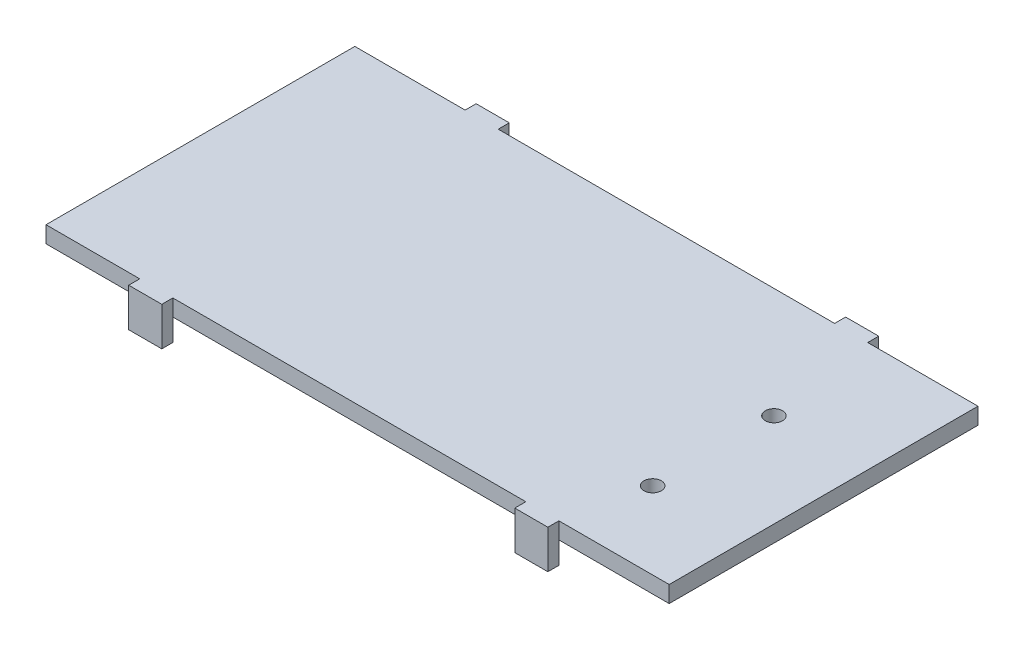
SolidWorks part; units mm, degrees
ref_plane "Front Plane" through (0, 0, 0) normal (0, 0, 1) x (1, 0, 0)
ref_plane "Top Plane" through (0, 0, 0) normal (0, 1, 0) x (1, 0, 0)
ref_plane "Right Plane" through (0, 0, 0) normal (1, 0, 0) x (0, 0, -1)
sketch "Sketch1" plane through (0, 0, 0) normal (0, 1, 0) x (1, 0, 0)
  line L1 (-75.3322, 26.3032) -> (68.1778, 26.3032)
  line L2 (-75.3322, 26.3032) -> (-75.3322, -44.8168)
  line L3 (-75.3322, -44.8168) -> (68.1778, -44.8168)
  line L4 (68.1778, 26.3032) -> (68.1778, -44.8168)
  dimension "D1" = 143.51
  dimension "D2" = 71.12
extrude "Boss-Extrude1" add sketch "Sketch1" along normal blind 3.81
sketch "Sketch2" plane through (0, 3.81, 0) normal (0, 1, 0) x (1, 0, 0)
  line L0 (68.1778, 26.3032) -> (-75.3322, 26.3032) construction
  line L1 (-49.9322, 26.3032) -> (-42.3122, 26.3032)
  line L2 (-49.9322, 26.3032) -> (-49.9322, 28.8432)
  line L3 (-49.9322, 28.8432) -> (-42.3122, 28.8432)
  line L4 (-42.3122, 26.3032) -> (-42.3122, 28.8432)
  line L5 (35.1578, 26.3032) -> (42.7778, 26.3032)
  line L6 (35.1578, 26.3032) -> (35.1578, 28.8432)
  line L7 (35.1578, 28.8432) -> (42.7778, 28.8432)
  line L8 (42.7778, 26.3032) -> (42.7778, 28.8432)
  line L9 (-53.7422, -47.3568) -> (-46.1222, -47.3568)
  line L10 (-53.7422, -47.3568) -> (-53.7422, -44.8168)
  line L11 (-53.7422, -44.8168) -> (-46.1222, -44.8168)
  line L12 (-46.1222, -47.3568) -> (-46.1222, -44.8168)
  line L13 (35.1578, -47.3568) -> (42.7778, -47.3568)
  line L14 (35.1578, -47.3568) -> (35.1578, -44.8168)
  line L15 (35.1578, -44.8168) -> (42.7778, -44.8168)
  line L16 (42.7778, -47.3568) -> (42.7778, -44.8168)
  line L17 (68.1778, -44.8168) -> (68.1778, 26.3032) construction
  line L18 (-75.3322, -44.8168) -> (68.1778, -44.8168) construction
  dimension "D1" = 7.62
  dimension "D2" = 2.54
  dimension "D3" = 0
  dimension "D4" = 2.54
  dimension "D5" = 7.62
  dimension "D6" = 7.62
  dimension "D7" = 2.54
  dimension "D8" = 7.62
  dimension "D9" = 2.54
  dimension "D10" = 25.4
  dimension "D11" = 0
  dimension "D12" = 0
  dimension "D13" = 121.92
extrude "Boss-Extrude3" add sketch "Sketch2" against normal blind 8.89
sketch "Sketch5" plane through (0, 0, 0) normal (0, -1, 0) x (-1, 0, 0)
  line L1 (46.1222, -44.8168) -> (-35.1578, -44.8168) construction
  line L2 (-68.1778, -44.8168) -> (-68.1778, 26.3032) construction
  circle A0 centre (-46.5878, -27.0368) radius 2
  circle A1 centre (-46.5878, 0.9032) radius 2
  point P4 (0, 0)
  point P7 (0, 0)
  point P8 (40.8348, -54.9753)
  point P9 (0, 0)
  point P12 (0, 0)
  dimension "D1" = 17.78
  dimension "D3" = 21.59
  dimension "D4" = 21.59
  dimension "D2" = 45.72
extrude "Cut-Extrude2" cut sketch "Sketch5" against normal through all
